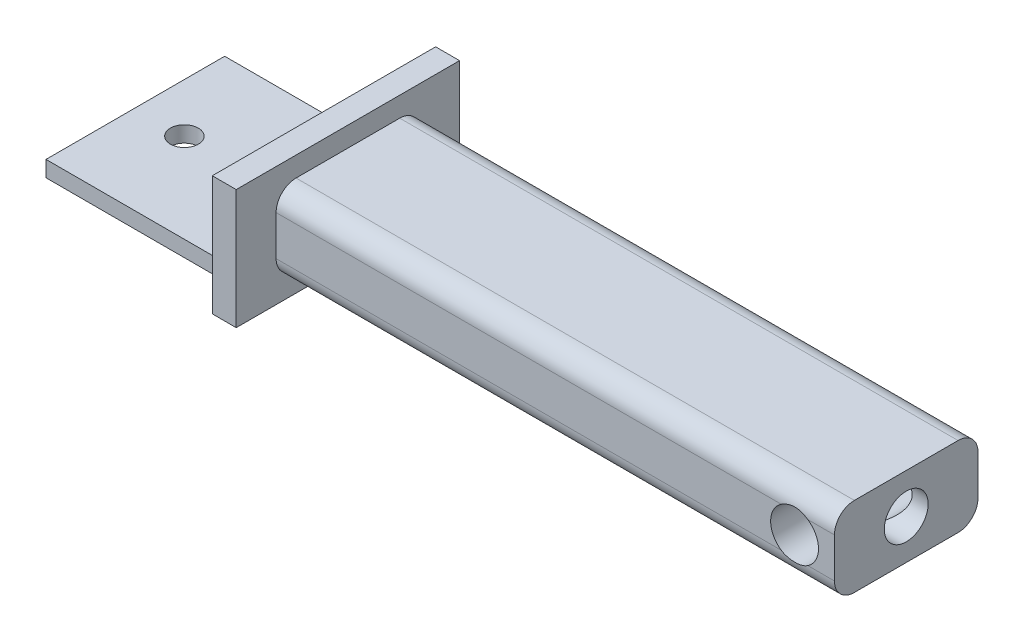
SolidWorks part; units mm, degrees
ref_plane "Piano frontale" through (0, 0, 0) normal (0, 0, 1) x (1, 0, 0)
ref_plane "Piano superiore" through (0, 0, 0) normal (0, 1, 0) x (1, 0, 0)
ref_plane "Piano destro" through (0, 0, 0) normal (1, 0, 0) x (0, 0, -1)
sketch "Schizzo1" plane through (0, 0, 0) normal (0, 1, 0) x (1, 0, 0)
  line L0 (-40.7097, 0) -> (39.8497, 0) construction
  line L2 (-35, 9) -> (35, 9)
  line L3 (-35, 9) -> (-35, -9)
  line L4 (-35, -9) -> (35, -9)
  line L5 (35, 9) -> (35, -9)
  line L6 (-35, 9) -> (35, -9) construction
  line L7 (-35, -9) -> (35, 9) construction
  point P3 (0, 0)
  dimension "D1" = 70
  dimension "D2" = 18
extrude "Estrusione-Estrusione1" add sketch "Schizzo1" along normal blind 10
fillet "Raccordo1" radius 2.5 1 edges at (0, 10, -9)
fillet "Raccordo2" radius 2.5 1 edges at (0, 10, 9)
fillet "Raccordo3" radius 2.5 1 edges at (0, 0, -9)
fillet "Raccordo4" radius 2.5 1 edges at (0, 0, 9)
hole_wizard "Foro per Vite 5/16-3" positions "Schizzo3D3" profile "Schizzo5" hole size "5/16" standard "Ansi Inch" end condition through all
sketch3d "Schizzo3D3"
  line L0 (-35, 7.5, -9) -> (35, 7.5, -9) construction
  line L1 (35, 7.5, -9) -> (35, 2.5, -9) construction
  point P0 (30, 5, -9)
  dimension "D1" = 2.5
  dimension "D2" = 5
sketch "Schizzo5" plane through (30, 5, -9) normal (1, 0, 0) x (0, 1, 0)
  line L0 (0, 0) -> (0, 18)
  line L1 (0, 18) -> (3, 18)
  line L2 (3, 18) -> (3, 0)
  line L5 (3, 0) -> (0, 0)
  line L11 (0, -6.35) -> (0, 107.95) construction
  dimension "Thru Hole Dia." = 6
  dimension "Thru Hole Depth" = 18
sketch "Schizzo6" plane through (-35, 0, 0) normal (-1, 0, 0) x (0, 0, 1)
  line L0 (0, 0) -> (0, 10) construction
  line L1 (-6.5, 0) -> (6.5, 0) construction
  line L2 (-6.5, 10) -> (6.5, 10) construction
  line L3 (-9, 5) -> (9, 5) construction
  line L4 (-9, 7.5) -> (-9, 2.5) construction
  line L5 (9, 7.5) -> (9, 2.5) construction
  line L7 (-14, -2.5) -> (14, -2.5)
  line L8 (-14, -2.5) -> (-14, 12.5)
  line L9 (-14, 12.5) -> (14, 12.5)
  line L10 (14, -2.5) -> (14, 12.5)
  line L11 (-14, -2.5) -> (14, 12.5) construction
  line L12 (-14, 12.5) -> (14, -2.5) construction
  point P12 (0, 5)
  dimension "D1" = 28
  dimension "D2" = 15
extrude "Estrusione-Estrusione2" add sketch "Schizzo6" along normal blind 3 contours L7 L10 L9 L8
hole_wizard "Foro svasato per Vite M2-1" positions "Schizzo7" profile "Schizzo8" countersink size "M2" standard "ISO"
sketch "Schizzo7" plane through (-35, 0, 0) normal (1, 0, 0) x (0, 0, -1)
  line L0 (0, -2.5) -> (0, 12.5) construction
  line L1 (14, -2.5) -> (-14, -2.5) construction
  line L2 (14, 12.5) -> (-14, 12.5) construction
  line L5 (14, -2.5) -> (14, 12.5) construction
  point P0 (-11.5, 5)
  point P2 (11.5, 5)
  dimension "D1" = 7.5
  dimension "D2" = 2.5
sketch "Schizzo8" plane through (-35, 5, 11.5) normal (0, 1, 0) x (0, 0, -1)
  line L0 (0, 0) -> (0, 6.721)
  line L1 (0, 6.721) -> (1.2, 6)
  line L2 (1.2, 6) -> (1.2, 1)
  line L3 (1.2, 1) -> (2.2, 0)
  line L5 (2.2, 0) -> (0, 0)
  line L6 (-1.2, 1) -> (-2.2, 0) construction
  line L10 (0, 6.721) -> (-1.2, 6) construction
  line L11 (0, -6.35) -> (0, 107.95) construction
  dimension "Hole Dia." = 2.4
  dimension "Hole Depth" = 6
  dimension "Near C'Sink Dia." = 4.4
  dimension "Near C'Sink Angle" = 90
  dimension "Drill Angle" = 118
hole_wizard "Foro per Vite M4-1" positions "Schizzo9" profile "Schizzo11" hole size "M4" standard "ISO" end condition through all
sketch "Schizzo9" plane through (-38, 0, 0) normal (-1, 0, 0) x (0, 0, 1)
  line L0 (14, 5) -> (-14, 5) construction
  line L1 (14, -2.5) -> (14, 12.5) construction
  line L2 (-14, -2.5) -> (-14, 12.5) construction
  line L4 (0, -2.5) -> (0, 12.5) construction
  line L5 (-14, -2.5) -> (14, -2.5) construction
  line L6 (-14, 12.5) -> (14, 12.5) construction
  point P17 (0, 5)
sketch "Schizzo11" plane through (-38, 5, 0) normal (0, 1, 0) x (0, 0, 1)
  line L0 (0, 0) -> (0, 73)
  line L1 (0, 73) -> (2.75, 73)
  line L2 (2.75, 73) -> (2.75, 0)
  line L5 (2.75, 0) -> (0, 0)
  line L11 (0, -6.35) -> (0, 107.95) construction
  dimension "Thru Hole Dia." = 5.5
  dimension "Thru Hole Depth" = 73
sketch "Schizzo12" plane through (-38, 0, 0) normal (-1, 0, 0) x (0, 0, 1)
  line L0 (0, -2.5) -> (0, 12.5) construction
  line L1 (-14, -2.5) -> (14, -2.5) construction
  line L2 (-14, 12.5) -> (14, 12.5) construction
  line L3 (14, -2.5) -> (14, 12.5) construction
  line L4 (11.2, -0.95) -> (-11.2, -0.95)
  line L5 (11.2, -0.95) -> (11.2, 1.05)
  line L6 (11.2, 1.05) -> (-11.2, 1.05)
  line L7 (-11.2, -0.95) -> (-11.2, 1.05)
  line L8 (11.2, -0.95) -> (-11.2, 1.05) construction
  line L9 (11.2, 1.05) -> (-11.2, -0.95) construction
  point P6 (0, 0.05)
  dimension "D1" = 2.8
  dimension "D2" = 2.55
  dimension "D3" = 2
extrude "Estrusione-Estrusione3" add sketch "Schizzo12" along normal blind 23.65
sketch "Schizzo13" plane through (0, -0.95, 0) normal (0, -1, 0) x (1, 0, 0)
  line L0 (-61.65, 0) -> (-38, 0) construction
  line L1 (-61.65, -11.2) -> (-61.65, 11.2) construction
  line L2 (-38, -11.2) -> (-38, 11.2) construction
  circle A0 centre (-55.5, 0) radius 1.75
  dimension "D2" = 3.5
  dimension "D1" = 17.5
extrude "Taglio-Estrusione1" cut sketch "Schizzo13" against normal blind 23.75
